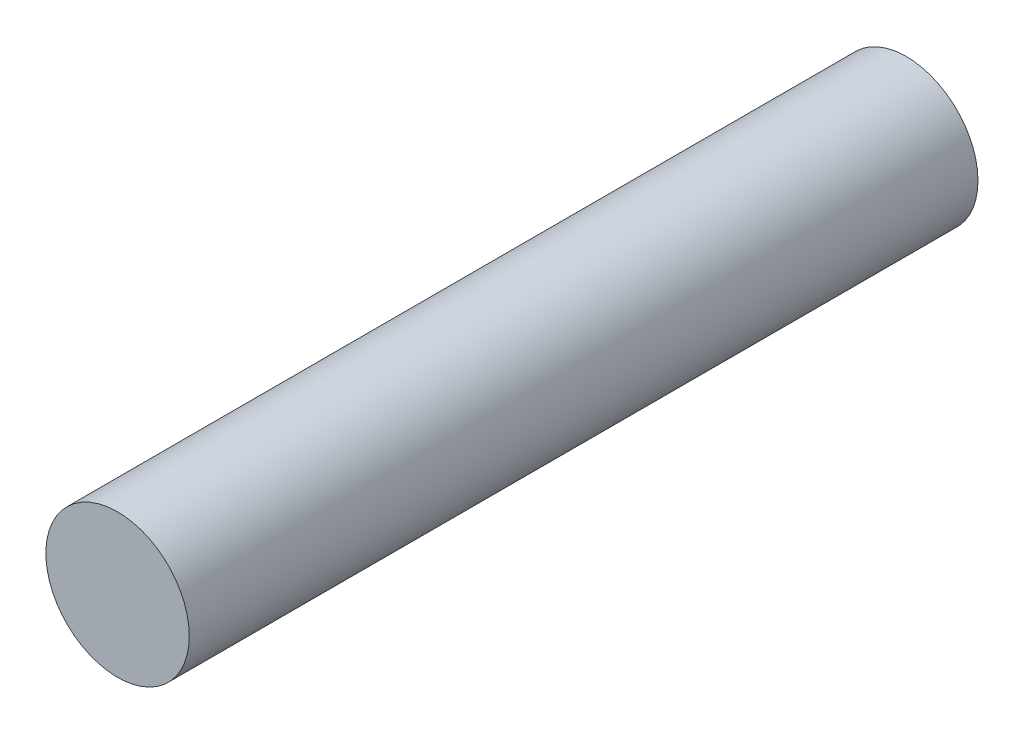
SolidWorks part; units mm, degrees
ref_plane "Front Plane" through (0, 0, 0) normal (0, 0, 1) x (1, 0, 0)
ref_plane "Top Plane" through (0, 0, 0) normal (0, 1, 0) x (1, 0, 0)
ref_plane "Right Plane" through (0, 0, 0) normal (1, 0, 0) x (0, 0, -1)
sketch "Sketch3" plane through (0, 0, 0) normal (0, 0, 1) x (1, 0, 0)
  circle A0 centre (-4.0687, 4.0687) radius 5
  dimension "D1" = 10
extrude "Boss-Extrude1" add sketch "Sketch3" along normal blind 55
